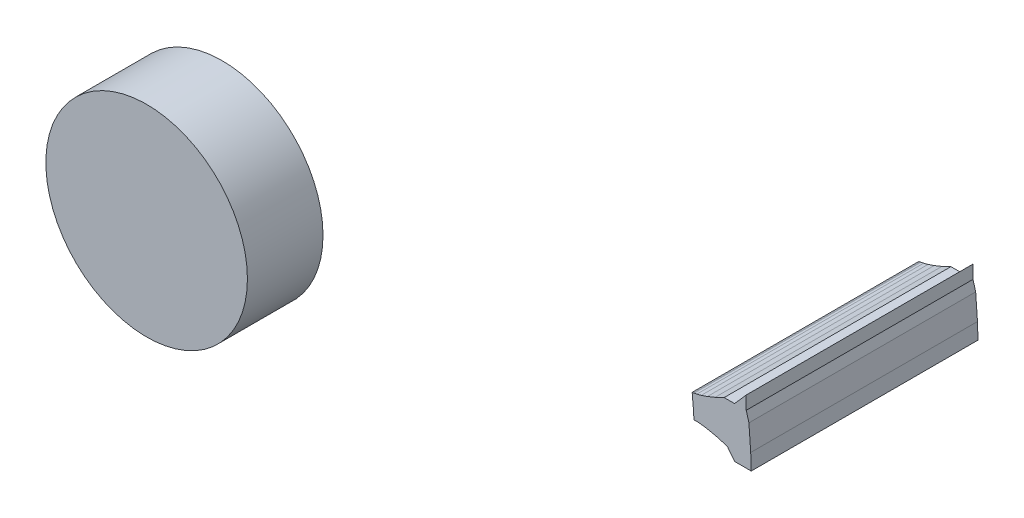
SolidWorks part; units mm, degrees
ref_plane "前视基准面" through (0, 0, 0) normal (0, 0, 1) x (1, 0, 0)
ref_plane "上视基准面" through (0, 0, 0) normal (0, 1, 0) x (1, 0, 0)
ref_plane "右视基准面" through (0, 0, 0) normal (1, 0, 0) x (0, 0, -1)
other "Configuration Table"
sketch "草图1" plane through (0, 0, 0) normal (0, 0, 1) x (1, 0, 0)
  circle A0 centre (0, 0) radius 8
extrude "凸台-拉伸1" add sketch "草图1" along normal blind 24
sketch "草图2" plane through (0, 0, 0) normal (0, 0, 1) x (1, 0, 0)
  circle A0 centre (0, 0) radius 42
extrude "凸台-拉伸2" add sketch "草图2" along normal blind 18
sketch "草图3" plane through (0, 0, 18) normal (0, 0, 1) x (1, 0, 0)
  line L0 (37.3016, 3.8521) -> (37.3889, 3.8612)
  line L1 (37.3889, 3.8612) -> (37.461, 3.8716)
  line L2 (37.461, 3.8716) -> (37.6754, 3.9151)
  line L3 (37.6754, 3.9151) -> (38.0276, 4.009)
  line L4 (38.0276, 4.009) -> (38.5116, 4.1707)
  line L5 (38.5116, 4.1707) -> (39.1199, 4.4167)
  line L6 (39.1199, 4.4167) -> (39.8432, 4.763)
  line L7 (39.8432, 4.763) -> (40.671, 4.763)
  line L8 (40.671, 4.763) -> (41.5954, 5.8158)
  line L9 (41.5954, 5.8158) -> (41.5954, 4.763)
  line L10 (41.5954, 4.763) -> (41.8082, 4.009)
  line L11 (41.8082, 4.009) -> (41.9504, 2.0408)
  line L12 (41.9504, 2.0408) -> (41.9927, 0.7845)
  line L13 (41.9927, 0.7845) -> (40.671, 0.7845)
  line L14 (40.671, 0.7845) -> (40.0978, 1.5285)
  line L15 (40.0978, 1.5285) -> (39.3292, 1.7573)
  line L16 (39.3292, 1.7573) -> (38.6899, 1.9052)
  line L17 (38.6899, 1.9052) -> (38.1865, 1.9892)
  line L18 (38.1865, 1.9892) -> (37.824, 2.0269)
  line L19 (37.824, 2.0269) -> (37.6055, 2.0362)
  line L20 (37.6055, 2.0362) -> (37.5326, 2.0353)
  line L21 (37.5326, 2.0353) -> (37.445, 2.0305)
  line L22 (37.445, 2.0305) -> (37.4175, 2.4866)
  line L23 (37.4175, 2.4866) -> (37.3844, 2.9422)
  line L24 (37.3844, 2.9422) -> (37.3016, 3.8521)
  circle A0 centre (0, 0) radius 42 construction
extrude "切除-拉伸1" cut sketch "草图3" against normal through all flip side to cut
